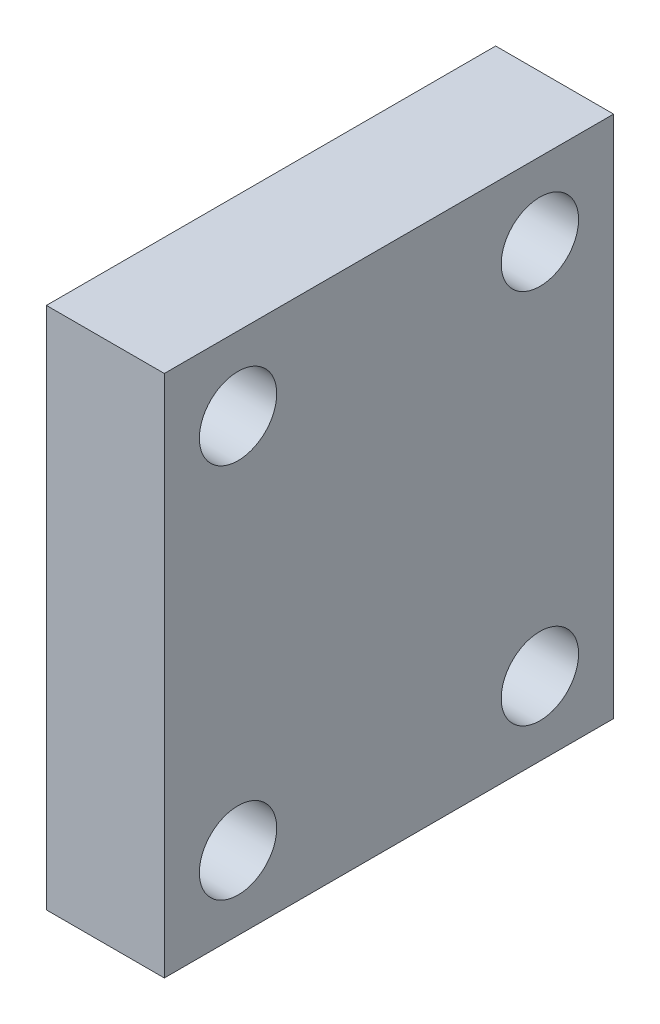
SolidWorks part; units mm, degrees
ref_plane "Front Plane" through (0, 0, 0) normal (1, 0, 0) x (0, 1, 0)
ref_plane "Top Plane" through (0, 0, 0) normal (0, 0, 1) x (0, 1, 0)
ref_plane "Right Plane" through (0, 0, 0) normal (0, 1, 0) x (-1, 0, 0)
sketch "Sketch1" plane through (0, 0, 0) normal (1, 0, 0) x (0, 1, 0)
  line L1 (0, 0) -> (112.776, 0)
  line L2 (0, 0) -> (0, 96.774)
  line L3 (0, 96.774) -> (112.776, 96.774)
  line L4 (112.776, 0) -> (112.776, 96.774)
extrude "Boss-Extrude1" add sketch "Sketch1" along normal blind 25.4
sketch "Sketch2" plane through (0, 0, 0) normal (1, 0, 0) x (0, 1, 0)
  circle A0 centre (15.875, 15.875) radius 8.3344
  circle A1 centre (96.901, 15.875) radius 8.3344
  circle A2 centre (15.875, 80.899) radius 8.3344
  circle A3 centre (96.901, 80.899) radius 8.3344
extrude "Cut-Extrude2" cut sketch "Sketch2" along normal through all
sketch "Sketch3" plane through (0, 0, 0) normal (1, 0, 0) x (0, 1, 0)
  circle A0 centre (28.575, 48.387) radius 11.5094
  circle A1 centre (74.549, 48.387) radius 11.5094
extrude "Cut-Extrude3" cut sketch "Sketch3" along normal blind 12.7
sketch "Sketch4" plane through (0, 0, 0) normal (1, 0, 0) x (0, 1, 0)
  circle A0 centre (38.227, 48.387) radius 11.5094
  circle A1 centre (84.201, 48.387) radius 11.5094
extrude "Cut-Extrude4" cut sketch "Sketch4" along normal blind 12.7
sketch "Sketch5" plane through (0, 0, 0) normal (1, 0, 0) x (0, 1, 0)
  circle A0 centre (38.227, 48.387) radius 16.6497
  circle A1 centre (84.201, 48.387) radius 16.6497
extrude "Cut-Extrude5" cut sketch "Sketch5" along normal blind 2.8194
sketch "Sketch6" plane through (0, 0, 0) normal (1, 0, 0) x (0, 1, 0)
  circle A0 centre (105.537, 48.387) radius 3.5719
  circle A1 centre (56.515, 15.875) radius 3.5719
extrude "Cut-Extrude6" cut sketch "Sketch6" along normal blind 7.874
sketch "Sketch7" plane through (0, 0, 0) normal (1, 0, 0) x (0, 1, 0)
  circle A0 centre (38.227, 48.387) radius 16.6497
sketch "Sketch8" plane through (0, 0, 0) normal (1, 0, 0) x (0, 1, 0)
  circle A0 centre (7.239, 48.387) radius 3.175
  circle A1 centre (56.261, 80.899) radius 3.175
extrude "Cut-Extrude9" cut sketch "Sketch8" along normal blind 7.874
sketch "Sketch9" plane through (0, 0, 0) normal (1, 0, 0) x (0, 1, 0)
  line L0 (0, 96.774) -> (0, 0) construction
  circle A0 centre (0, 56.388) radius 3.175
extrude "Boss-Extrude2" add sketch "Sketch9" along normal blind 12.7
